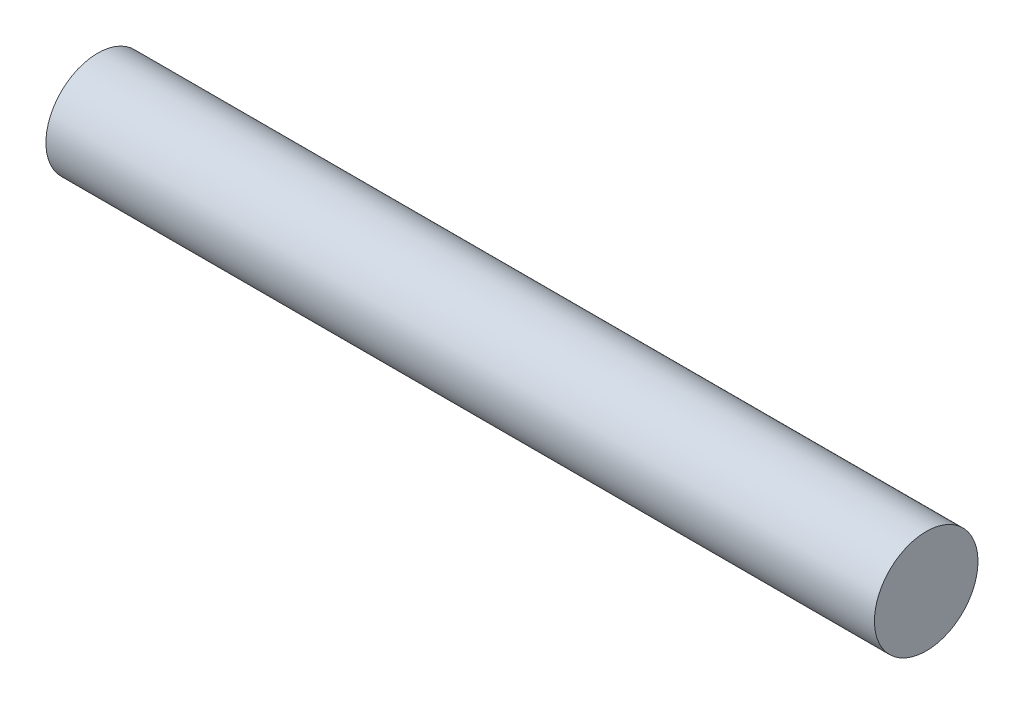
SolidWorks part; units mm, degrees
ref_plane "Front Plane" through (0, 0, 0) normal (1, 0, 0) x (0, 1, 0)
ref_plane "Top Plane" through (0, 0, 0) normal (0, 0, 1) x (0, 1, 0)
ref_plane "Right Plane" through (0, 0, 0) normal (0, 1, 0) x (-1, 0, 0)
sketch "Sketch1" plane through (0, 0, 0) normal (1, 0, 0) x (0, 1, 0)
  circle A0 centre (0, 0) radius 1.5875
  dimension "D1" = 3.175
extrude "Boss-Extrude1" add sketch "Sketch1" along normal blind 25.4
equation "\"shaft_len\"= 1in"
equation "\"ouput_shaft_d\"= 0.25"
equation "\"input_shaft_d\"= 0.125in"
equation "\"pinion_pitch\"= 3 / 8in"
equation "\"gear_pitch\"= 1in"
equation "\"pitch_tot\"= \"pinion_pitch\" + \"gear_pitch\""
equation "\"sleeve_len\"= 3 / 8in"
equation "\"pinion_sleeve_d\"= 1 / 4in"
equation "\"gear_sleeve_d\"= 3 / 8in"
equation "\"D1@Sketch1\"=\"input_shaft_d\""
equation "\"D1@Boss-Extrude1\"=\"shaft_len\""
